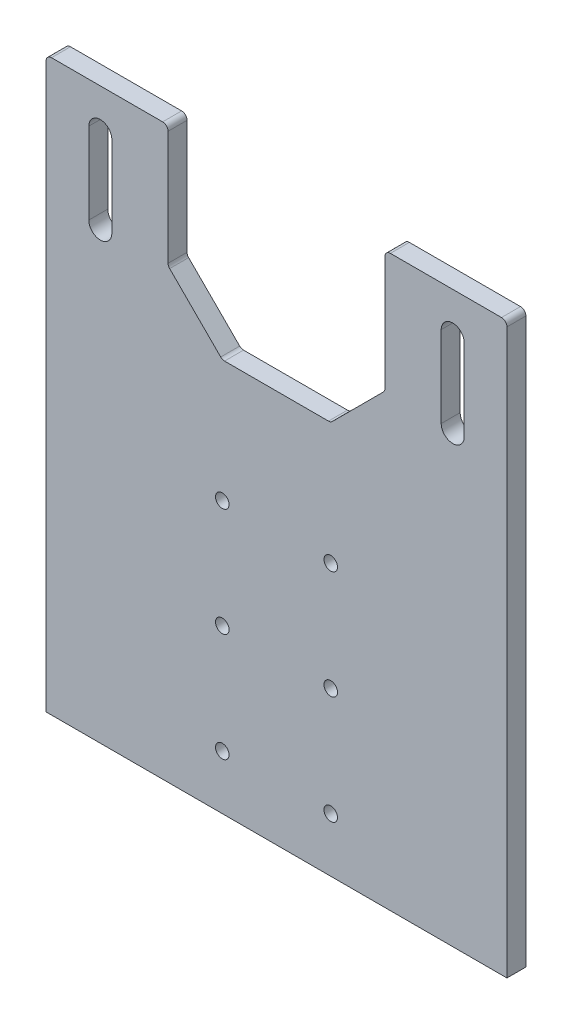
SolidWorks part; units mm, degrees
ref_plane "Front Plane" through (0, 0, 0) normal (0, 0, 1) x (1, 0, 0)
ref_plane "Top Plane" through (0, 0, 0) normal (0, 1, 0) x (1, 0, 0)
ref_plane "Right Plane" through (0, 0, 0) normal (1, 0, 0) x (0, 0, -1)
sketch "Sketch1" plane through (0, 0, 0) normal (0, 0, 1) x (1, 0, 0)
  line L22 (85, 223.351) -> (85, 0) construction
  line L23 (0, 210) -> (45, 210)
  line L24 (0, 210) -> (0, 0)
  line L25 (0, 0) -> (170, 0)
  line L26 (170, 210) -> (170, 0)
  line L27 (105, 145) -> (65, 145)
  line L28 (65, 145) -> (45, 165)
  line L29 (45, 165) -> (45, 210)
  line L30 (125, 165) -> (125, 210)
  line L31 (105, 145) -> (125, 165)
  line L32 (125, 210) -> (170, 210)
  line L33 (125, 210) -> (45, 210) construction
  line L34 (65, 0) -> (65, 210) construction
  line L35 (150, 195) -> (150, 165) construction
  line L36 (154.25, 195) -> (154.25, 165)
  line L37 (145.75, 195) -> (145.75, 165)
  line L38 (20, 195) -> (20, 165) construction
  line L39 (15.75, 195) -> (15.75, 165)
  line L40 (24.25, 195) -> (24.25, 165)
  circle A10 centre (65, 20) radius 2.5
  circle A11 centre (65, 60) radius 2.5
  circle A12 centre (65, 100) radius 2.5
  circle A13 centre (105, 100) radius 2.5
  circle A14 centre (105, 60) radius 2.5
  circle A15 centre (105, 20) radius 2.5
  arc A16 (154.25, 195) -> (145.75, 195) centre (150, 195) ccw
  arc A17 (145.75, 165) -> (154.25, 165) centre (150, 165) ccw
  arc A18 (15.75, 195) -> (24.25, 195) centre (20, 195) cw
  arc A19 (24.25, 165) -> (15.75, 165) centre (20, 165) cw
  point P59 (85, 145)
  point P63 (150, 180)
  point P82 (20, 180)
  dimension "D21" = 5
  dimension "D18" = 210
  dimension "D19" = 170
  dimension "D20" = 135
  dimension "D22" = 20
  dimension "D24" = 40
  dimension "D25" = 40
  dimension "D26" = 45
  dimension "D27" = 30
  dimension "D28" = 15
  dimension "D29" = 8.5
  dimension "D30" = 20
  dimension "D31" = 65
  dimension "D23" = 3
extrude "Boss-Extrude1" add sketch "Sketch1" along normal blind 12
sketch "Sketch3" plane through (0, 0, 0) normal (0, 0, -1) x (-1, 0, 0)
  line L0 (-45, 210) -> (0, 210) construction
  line L1 (0, 0) -> (-55, 0)
  line L2 (0, 0) -> (0, 210)
  line L3 (0, 210) -> (-55, 210)
  line L4 (-55, 0) -> (-55, 115)
  line L5 (-170, 0) -> (-115, 0)
  line L6 (-170, 0) -> (-170, 210)
  line L7 (-170, 210) -> (-115, 210)
  line L8 (-115, 0) -> (-115, 115)
  line L10 (-115, 210) -> (-55, 210)
  line L12 (-115, 115) -> (-55, 115)
  dimension "D1" = 60
  dimension "D2" = 95
extrude "Cut-Extrude1" cut sketch "Sketch3" against normal blind 5
fillet "Fillet1" radius 2 8 edges at (170, 210, 8.5) (125, 210, 8.5) (125, 165, 8.5) (105, 145, 8.5) (65, 145, 8.5) (45, 165, 8.5) (45, 210, 8.5) (0, 210, 8.5)
sketch "Sketch4" plane through (0, 0, 0) normal (0, -1, 0) x (1, 0, 0)
  line L0 (170, 8.5) -> (0, 8.5) construction
  line L1 (170, 12) -> (170, 5) construction
  line L2 (0, 12) -> (0, 5) construction
  line L3 (115, 6) -> (55, 6) construction
  line L4 (115, 5) -> (115, 0) construction
  line L5 (55, 5) -> (55, 0) construction
  line L6 (0, 12) -> (170, 12) construction
  line L7 (85, 0) -> (85, 12) construction
  line L8 (55, 0) -> (115, 0) construction
  circle A0 centre (85, 6) radius 1.5
  circle A1 centre (105, 6) radius 1.5
  circle A2 centre (155, 8.5) radius 1.5
  circle A3 centre (125, 8.5) radius 1.5
  circle A4 centre (15, 8.5) radius 1.5
  circle A5 centre (45, 8.5) radius 1.5
  circle A6 centre (65, 6) radius 1.5
  dimension "D2" = 3
  dimension "D1" = 6
  dimension "D3" = 20
  dimension "D4" = 20
  dimension "D5" = 30
extrude "Cut-Extrude2" cut sketch "Sketch4" against normal blind 5
